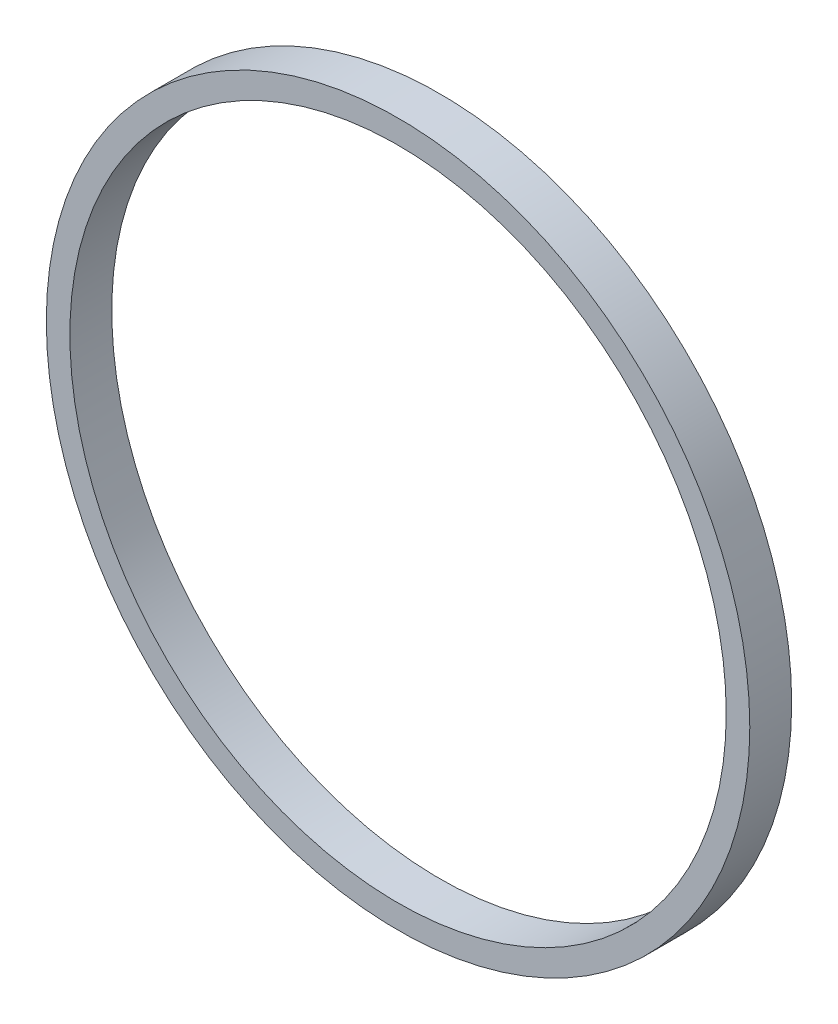
SolidWorks part; units mm, degrees
ref_plane "Front Plane" through (0, 0, 0) normal (0, 0, 1) x (1, 0, 0)
ref_plane "Top Plane" through (0, 0, 0) normal (0, 1, 0) x (1, 0, 0)
ref_plane "Right Plane" through (0, 0, 0) normal (1, 0, 0) x (0, 0, -1)
sketch "Sketch1" plane through (0, 0, 0) normal (0, 0, 1) x (1, 0, 0)
  circle A0 centre (0, 0) radius 26.87
  circle A1 centre (0, 0) radius 25.07
  dimension "D1" = 53.74
  dimension "D2" = 1.8
extrude "Boss-Extrude1" add sketch "Sketch1" along normal blind 3.2
